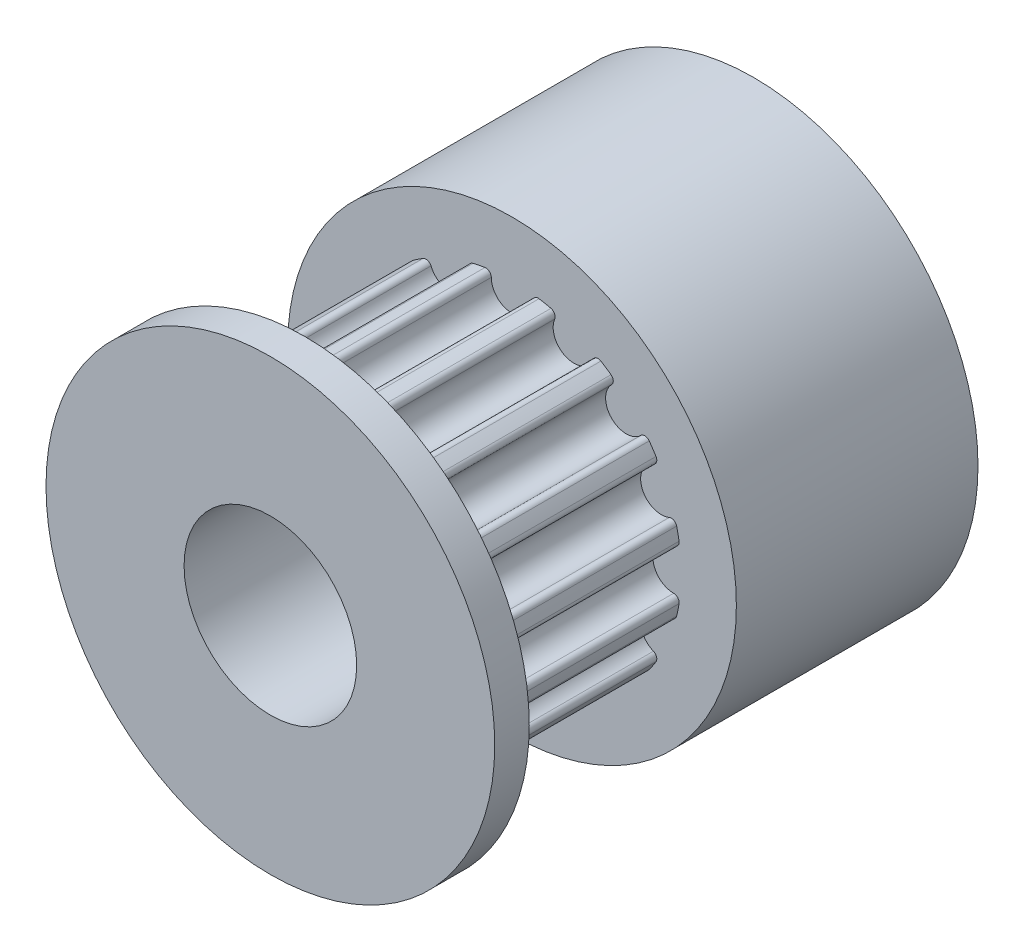
SolidWorks part; units mm, degrees
ref_plane "前视基准面" through (0, 0, 0) normal (0, 0, 1) x (1, 0, 0)
ref_plane "上视基准面" through (0, 0, 0) normal (0, 1, 0) x (1, 0, 0)
ref_plane "右视基准面" through (0, 0, 0) normal (1, 0, 0) x (0, 0, -1)
sketch "草图1" plane through (0, 0, 0) normal (0, 0, 1) x (1, 0, 0)
  circle A0 centre (0, 0) radius 6.5
  dimension "D1" = 13
extrude "凸台-拉伸1" add sketch "草图1" along normal blind 7
sketch "草图2" plane through (0, 0, 7) normal (0, 0, 1) x (1, 0, 0)
  arc B0 (-0.6, 4.6835) -> (-0.7833, 4.8395) centre (-0.758, 4.6835) ccw
  arc B1 (-0.6, 4.6835) -> (0.6, 4.6835) centre (0, 4.6835) ccw
  arc B2 (0.7833, 4.8395) -> (0.6, 4.6835) centre (0.758, 4.6835) ccw
  arc B3 (1.1283, 4.7708) -> (0.7833, 4.8395) centre (0, 0) ccw
  arc B4 (1.238, 4.5566) -> (1.1283, 4.7708) centre (1.0919, 4.617) ccw
  arc B5 (1.238, 4.5566) -> (2.3466, 4.0973) centre (1.7923, 4.327) ccw
  arc B6 (2.5757, 4.1713) -> (2.3466, 4.0973) centre (2.4926, 4.0369) ccw
  arc B7 (2.8681, 3.9759) -> (2.5757, 4.1713) centre (0, 0) ccw
  arc B8 (2.8874, 3.736) -> (2.8681, 3.9759) centre (2.7757, 3.8477) ccw
  arc B9 (2.8874, 3.736) -> (3.736, 2.8874) centre (3.3117, 3.3117) ccw
  arc B10 (3.9759, 2.8681) -> (3.736, 2.8874) centre (3.8477, 2.7757) ccw
  arc B11 (4.1713, 2.5757) -> (3.9759, 2.8681) centre (0, 0) ccw
  arc B12 (4.0973, 2.3466) -> (4.1713, 2.5757) centre (4.0369, 2.4926) ccw
  arc B13 (4.0973, 2.3466) -> (4.5566, 1.238) centre (4.327, 1.7923) ccw
  arc B14 (4.7708, 1.1283) -> (4.5566, 1.238) centre (4.617, 1.0919) ccw
  arc B15 (4.8395, 0.7833) -> (4.7708, 1.1283) centre (0, 0) ccw
  arc B16 (4.6835, 0.6) -> (4.8395, 0.7833) centre (4.6835, 0.758) ccw
  arc B17 (4.6835, 0.6) -> (4.6835, -0.6) centre (4.6835, 0) ccw
  arc B18 (4.8395, -0.7833) -> (4.6835, -0.6) centre (4.6835, -0.758) ccw
  arc B19 (4.7708, -1.1283) -> (4.8395, -0.7833) centre (0, 0) ccw
  arc B20 (4.5566, -1.238) -> (4.7708, -1.1283) centre (4.617, -1.0919) ccw
  arc B21 (4.5566, -1.238) -> (4.0973, -2.3466) centre (4.327, -1.7923) ccw
  arc B22 (3.9759, -2.8681) -> (4.1713, -2.5757) centre (0, 0) ccw
  arc B23 (3.736, -2.8874) -> (3.9759, -2.8681) centre (3.8477, -2.7757) ccw
  arc B24 (3.736, -2.8874) -> (2.8874, -3.736) centre (3.3117, -3.3117) ccw
  arc B25 (2.8681, -3.9759) -> (2.8874, -3.736) centre (2.7757, -3.8477) ccw
  arc B26 (2.5757, -4.1713) -> (2.8681, -3.9759) centre (0, 0) ccw
  arc B27 (2.3466, -4.0973) -> (2.5757, -4.1713) centre (2.4926, -4.0369) ccw
  arc B28 (2.3466, -4.0973) -> (1.238, -4.5566) centre (1.7923, -4.327) ccw
  arc B29 (1.1283, -4.7708) -> (1.238, -4.5566) centre (1.0919, -4.617) ccw
  arc B30 (0.7833, -4.8395) -> (1.1283, -4.7708) centre (0, 0) ccw
  arc B31 (0.6, -4.6835) -> (0.7833, -4.8395) centre (0.758, -4.6835) ccw
  arc B32 (0.6, -4.6835) -> (-0.6, -4.6835) centre (0, -4.6835) ccw
  arc B33 (-0.7833, -4.8395) -> (-0.6, -4.6835) centre (-0.758, -4.6835) ccw
  arc B34 (-1.1283, -4.7708) -> (-0.7833, -4.8395) centre (0, 0) ccw
  arc B35 (-1.238, -4.5566) -> (-1.1283, -4.7708) centre (-1.0919, -4.617) ccw
  arc B36 (-1.238, -4.5566) -> (-2.3466, -4.0973) centre (-1.7923, -4.327) ccw
  arc B37 (-2.5757, -4.1713) -> (-2.3466, -4.0973) centre (-2.4926, -4.0369) ccw
  arc B38 (-2.8681, -3.9759) -> (-2.5757, -4.1713) centre (0, 0) ccw
  arc B39 (-2.8874, -3.736) -> (-2.8681, -3.9759) centre (-2.7757, -3.8477) ccw
  arc B40 (-2.8874, -3.736) -> (-3.736, -2.8874) centre (-3.3117, -3.3117) ccw
  arc B41 (-3.9759, -2.8681) -> (-3.736, -2.8874) centre (-3.8477, -2.7757) ccw
  arc B42 (-4.1713, -2.5757) -> (-3.9759, -2.8681) centre (0, 0) ccw
  arc B43 (-4.0973, -2.3466) -> (-4.1713, -2.5757) centre (-4.0369, -2.4926) ccw
  arc B44 (-4.0973, -2.3466) -> (-4.5566, -1.238) centre (-4.327, -1.7923) ccw
  arc B45 (-4.7708, -1.1283) -> (-4.5566, -1.238) centre (-4.617, -1.0919) ccw
  arc B46 (-4.8395, -0.7833) -> (-4.7708, -1.1283) centre (0, 0) ccw
  arc B47 (-4.6835, -0.6) -> (-4.8395, -0.7833) centre (-4.6835, -0.758) ccw
  arc B48 (-4.6835, -0.6) -> (-4.6835, 0.6) centre (-4.6835, 0) ccw
  arc B49 (-4.8395, 0.7833) -> (-4.6835, 0.6) centre (-4.6835, 0.758) ccw
  arc B50 (-4.7708, 1.1283) -> (-4.8395, 0.7833) centre (0, 0) ccw
  arc B51 (-4.5566, 1.238) -> (-4.7708, 1.1283) centre (-4.617, 1.0919) ccw
  arc B52 (-4.5566, 1.238) -> (-4.0973, 2.3466) centre (-4.327, 1.7923) ccw
  arc B53 (-4.1713, 2.5757) -> (-4.0973, 2.3466) centre (-4.0369, 2.4926) ccw
  arc B54 (-3.9759, 2.8681) -> (-4.1713, 2.5757) centre (0, 0) ccw
  arc B55 (-3.736, 2.8874) -> (-3.9759, 2.8681) centre (-3.8477, 2.7757) ccw
  arc B56 (-3.736, 2.8874) -> (-2.8874, 3.736) centre (-3.3117, 3.3117) ccw
  arc B57 (-2.8681, 3.9759) -> (-2.8874, 3.736) centre (-2.7757, 3.8477) ccw
  arc B58 (-2.5757, 4.1713) -> (-2.8681, 3.9759) centre (0, 0) ccw
  arc B59 (-2.3466, 4.0973) -> (-2.5757, 4.1713) centre (-2.4926, 4.0369) ccw
  arc B60 (-2.3466, 4.0973) -> (-1.238, 4.5566) centre (-1.7923, 4.327) ccw
  arc B61 (-1.1283, 4.7708) -> (-1.238, 4.5566) centre (-1.0919, 4.617) ccw
  arc B62 (-0.7833, 4.8395) -> (-1.1283, 4.7708) centre (0, 0) ccw
  arc B63 (4.1713, -2.5757) -> (4.0973, -2.3466) centre (4.0369, -2.4926) ccw
sketch_block_instance "2GT-16-1"
sketch_block "2GT-16"
extrude "凸台-拉伸2" add sketch "草图2" along normal blind 6
sketch "草图4" plane through (0, 0, 13) normal (0, 0, 1) x (1, 0, 0)
  circle A0 centre (0, 0) radius 6.5 construction
  circle A1 centre (0, 0) radius 6.5
extrude "凸台-拉伸3" add sketch "草图4" along normal blind 1
sketch "草图5" plane through (0, 0, 0) normal (0, 0, -1) x (-1, 0, 0)
  circle A0 centre (0, 0) radius 2.5
  dimension "D1" = 5
extrude "切除-拉伸1" cut sketch "草图5" against normal through all
